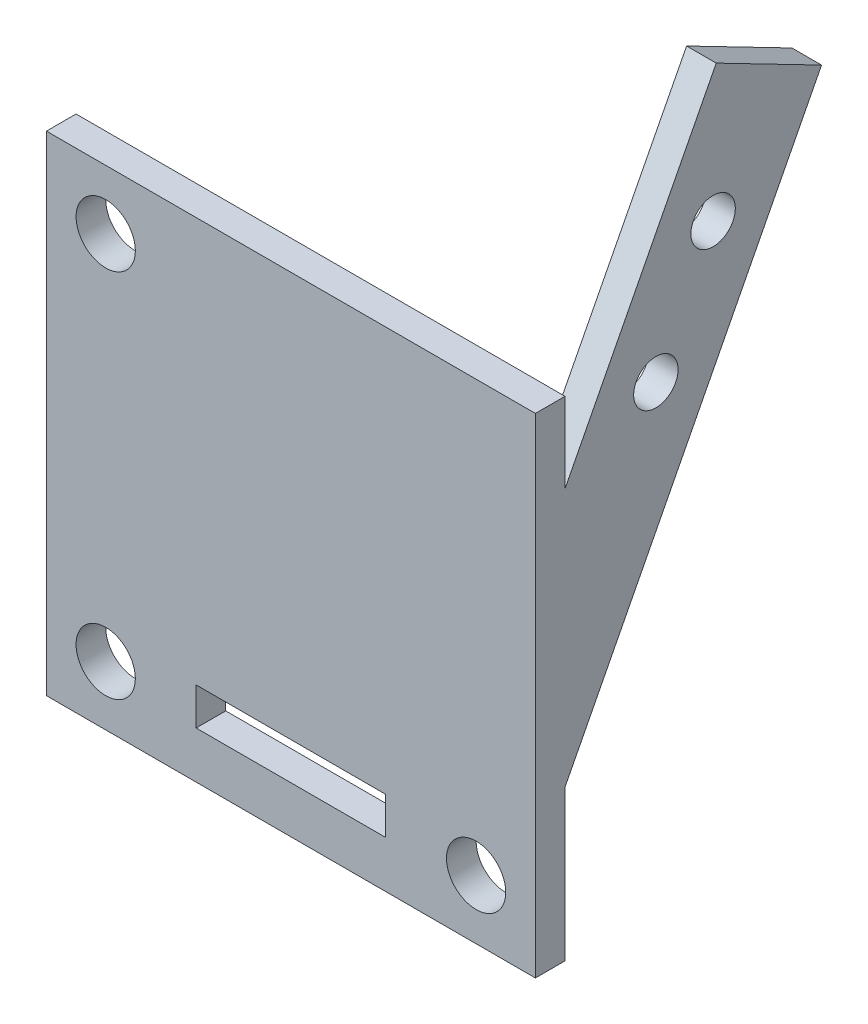
SolidWorks part; units mm, degrees
ref_plane "Front Plane" through (0, 0, 0) normal (0, 0, 1) x (1, 0, 0)
ref_plane "Top Plane" through (0, 0, 0) normal (0, 1, 0) x (1, 0, 0)
ref_plane "Right Plane" through (0, 0, 0) normal (1, 0, 0) x (0, 0, -1)
sketch "Sketch2" plane through (0, 0, 0) normal (0, 0, 1) x (1, 0, 0)
  line L1 (-16.5, 16.5) -> (16.5, 16.5)
  line L2 (-16.5, 16.5) -> (-16.5, -16.5)
  line L3 (-16.5, -16.5) -> (16.5, -16.5)
  line L4 (16.5, 16.5) -> (16.5, -16.5)
  line L5 (-16.5, 16.5) -> (16.5, -16.5) construction
  line L6 (-16.5, -16.5) -> (16.5, 16.5) construction
  point P0 (0, 0)
  dimension "D1" = 33
extrude "Boss-Extrude1" add sketch "Sketch2" along normal blind 2
sketch "Sketch3" plane through (16.5, 0, 0) normal (1, 0, 0) x (0, 0, -1)
  line L0 (0, 2.379) -> (13.7595, 29.0375) construction
  line L1 (0, -16.5) -> (0, 16.5) construction
  line L2 (-3.5545, 4.2136) -> (10.205, 30.8721) construction
  line L3 (3.5545, 0.5444) -> (0, -6.3423)
  line L4 (3.5545, 0.5444) -> (17.314, 27.2029)
  line L6 (0, 11.1002) -> (10.205, 30.8721)
  line L7 (10.205, 30.8721) -> (17.314, 27.2029)
  line L8 (0, 11.1002) -> (0, -6.3423)
  line L9 (3.5545, 0.5444) -> (-10.205, -26.1141) construction
  line L10 (0, 2.379) -> (-13.7595, -24.2796) construction
  line L11 (-3.5545, 4.2136) -> (-17.314, -22.445) construction
  dimension "D1" = 27.3
  dimension "D3" = 4
  dimension "D4" = 4
extrude "Boss-Extrude2" add sketch "Sketch3" against normal blind 2
sketch "Sketch4" plane through (16.5, 0, 0) normal (1, 0, 0) x (0, 0, -1)
  line L0 (0, 2.379) -> (13.7595, 29.0375) construction
  circle A0 centre (6.1315, 14.2586) radius 1.5
  circle A1 centre (9.9945, 21.743) radius 1.5
extrude "Cut-Extrude1" cut sketch "Sketch4" against normal up to surface (2 mm away) up to face at (14.5, 15.7082, -6.8797)
sketch "Sketch5" plane through (0, 0, 0) normal (0, 0, -1) x (-1, 0, 0)
  line L1 (-6.3991, -10.8176) -> (6.3991, -10.8176)
  line L2 (-6.3991, -10.8176) -> (-6.3991, -13.3374)
  line L3 (-6.3991, -13.3374) -> (6.3991, -13.3374)
  line L4 (6.3991, -10.8176) -> (6.3991, -13.3374)
  line L5 (-6.3991, -10.8176) -> (6.3991, -13.3374) construction
  line L6 (-6.3991, -13.3374) -> (6.3991, -10.8176) construction
  circle A1 centre (12.5, 12.5) radius 2
  circle A2 centre (12.5, -12.5) radius 2
  circle A3 centre (-12.5, -12.5) radius 2
  point P0 (0, -12.0775)
  dimension "D1" = 2.5198
  dimension "D2" = 12.7981
extrude "Cut-Extrude2" cut sketch "Sketch5" against normal up to surface (2 mm away) up to face at (0, 0, 2)
